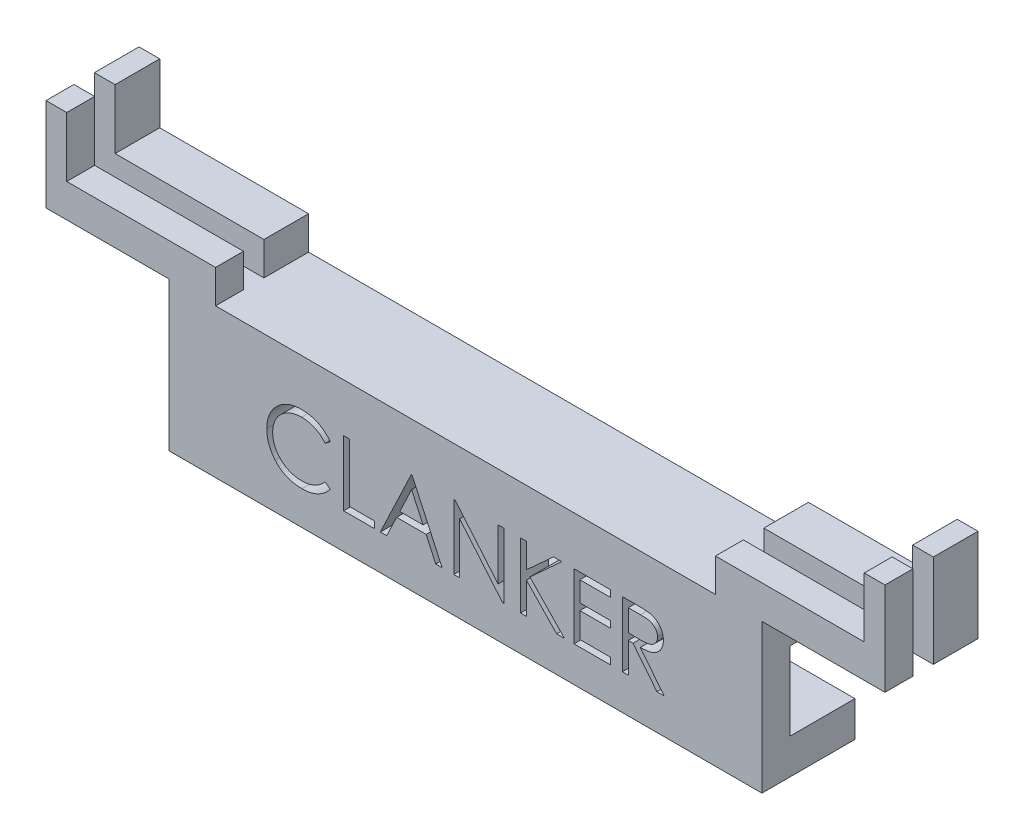
SolidWorks part; units mm, degrees
ref_plane "Front Plane" through (0, 0, 0) normal (0, 0, 1) x (1, 0, 0)
ref_plane "Top Plane" through (0, 0, 0) normal (0, 1, 0) x (1, 0, 0)
ref_plane "Right Plane" through (0, 0, 0) normal (1, 0, 0) x (0, 0, -1)
sketch "Sketch2" plane through (0, 0, 0) normal (0, 0, 1) x (1, 0, 0)
  line L0 (21.4353, 2.5) -> (21.4353, -0.7101)
  line L1 (-22.55, 2.5) -> (-21.4353, 2.5)
  line L2 (-22.55, 2.5) -> (-22.55, -2.5)
  line L3 (-22.55, -2.5) -> (-13.4354, -2.5)
  line L4 (22.55, 2.5) -> (22.55, -2.5)
  line L5 (-22.55, 2.5) -> (-21.4353, 2.3764) construction
  line L6 (-22.55, -2.5) -> (-13.4354, -1.4895) construction
  line L7 (21.4353, -0.7101) -> (13.4354, -0.7101)
  line L8 (13.4354, -0.7101) -> (13.4354, -2.5)
  line L9 (0, 0) -> (0, 5.8213) construction
  line L10 (-21.4353, 2.5) -> (-21.4353, -0.7101)
  line L11 (-21.4353, -0.7101) -> (-13.4354, -0.7101)
  line L12 (-13.4354, -0.7101) -> (-13.4354, -2.5)
  line L13 (21.4353, 2.5) -> (22.55, 2.5)
  line L14 (13.4354, -1.4895) -> (22.55, -2.5) construction
  line L15 (21.4353, 2.3764) -> (22.55, 2.5) construction
  line L16 (13.4354, -2.5) -> (22.55, -2.5)
  point P0 (0, 0)
  dimension "D1" = 45.1
  dimension "D2" = 5
extrude "Boss-Extrude1" add sketch "Sketch2" against normal blind 5
sketch "Sketch4" plane through (0, 0, 0) normal (0, 0, 1) x (1, 0, 0)
  line L0 (-13.4354, -2.5) -> (-15.9354, -2.5) construction
  line L1 (-22.55, -2.5) -> (-13.4354, -2.5) construction
  line L2 (13.4354, -2.5) -> (15.9354, -2.5) construction
  line L3 (13.4354, -2.5) -> (22.55, -2.5) construction
  line L5 (-15.9354, -2.5) -> (15.9354, -2.5)
  line L6 (-15.9354, -2.5) -> (-15.9354, -10.5)
  line L7 (-15.9354, -10.5) -> (15.9354, -10.5)
  line L8 (15.9354, -2.5) -> (15.9354, -10.5)
  dimension "D1" = 2.5
  dimension "D2" = 2.5
  dimension "D3" = 8
extrude "Boss-Extrude2" add sketch "Sketch4" against normal blind 5
sketch "Sketch5" plane through (0, 0, -5) normal (0, 0, -1) x (-1, 0, 0)
  line L0 (0, -10.5) -> (0, -1.4976) construction
  line L1 (15.9354, -10.5) -> (-15.9354, -10.5) construction
  line L3 (-16.3381, -4.4) -> (16.3381, -4.4)
  line L4 (-16.3381, -4.4) -> (-16.3381, -8.6)
  line L5 (-16.3381, -8.6) -> (16.3381, -8.6)
  line L6 (16.3381, -4.4) -> (16.3381, -8.6)
  line L7 (-16.3381, -4.4) -> (16.3381, -8.6) construction
  line L8 (-16.3381, -8.6) -> (16.3381, -4.4) construction
  point P5 (0, -6.5)
  dimension "D1" = 4.2
extrude "Cut-Extrude1" cut sketch "Sketch5" against normal blind 3.5
sketch "Sketch6" plane through (0, 2.5, 0) normal (0, 1, 0) x (1, 0, 0)
  line L0 (22.55, 5) -> (22.55, 0) construction
  line L1 (-22.55, 1.5) -> (22.55, 1.5)
  line L2 (-22.55, 1.5) -> (-22.55, 2.6)
  line L3 (-22.55, 2.6) -> (22.55, 2.6)
  line L4 (22.55, 1.5) -> (22.55, 2.6)
  line L5 (-22.55, 1.5) -> (22.55, 2.6) construction
  line L6 (-22.55, 2.6) -> (22.55, 1.5) construction
  line L7 (13.4354, 0) -> (-13.4354, 0) construction
  point P0 (0, 2.05)
  point P7 (0, 0)
  point P8 (0, 0)
  point P9 (0, 1.8117)
  dimension "D1" = 1.5
  dimension "D2" = 1.1
extrude "Cut-Extrude2" cut sketch "Sketch6" against normal blind 5
sketch "Sketch7" plane through (0, 0, 0) normal (0, 0, 1) x (1, 0, 0)
  line L0 (-15.9354, -8.6) -> (15.9354, -8.6) construction
  line L1 (15.9354, -10.5) -> (15.9354, -2.5) construction
  text T0 "CLANKER"
extrude "Cut-Extrude3" cut sketch "Sketch7" against normal blind 3
